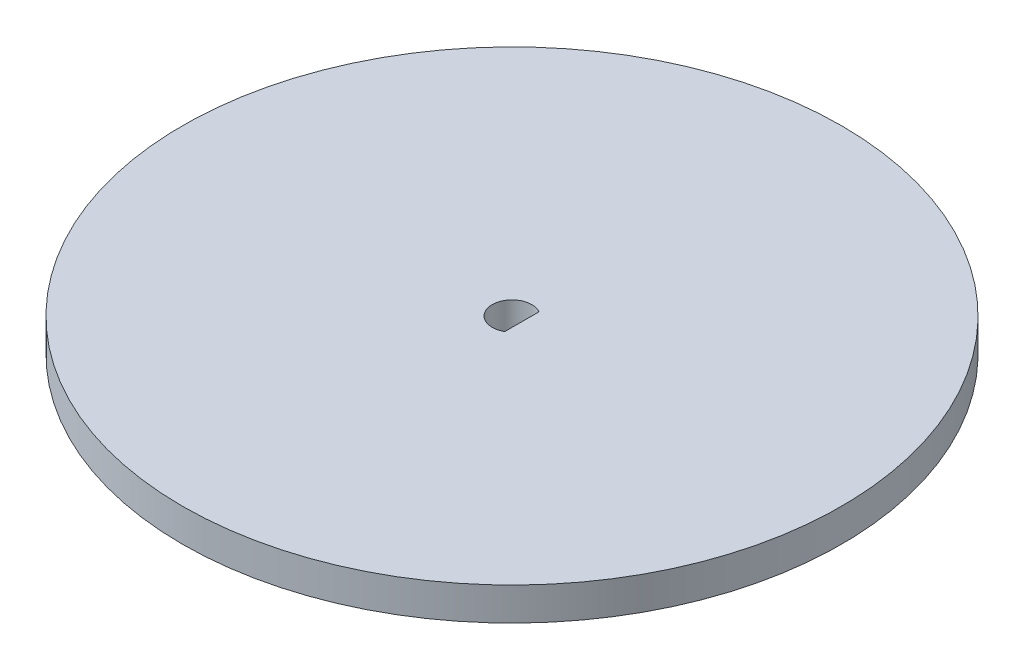
SolidWorks part; units mm, degrees
ref_plane "前视基准面" through (0, 0, 0) normal (0, 0, 1) x (1, 0, 0)
ref_plane "上视基准面" through (0, 0, 0) normal (0, 1, 0) x (1, 0, 0)
ref_plane "右视基准面" through (0, 0, 0) normal (1, 0, 0) x (0, 0, -1)
sketch "Sketch1" plane through (0, 0, 0) normal (0, 1, 0) x (1, 0, 0)
  line L0 (1.5, 4.1874) -> (1.5, -5.6419) construction
  line L1 (1.5, 2.5981) -> (1.5, -2.5981)
  line L2 (-50, 0) -> (25.889, 0) construction
  line L3 (0, 50) -> (0, -50) construction
  circle A0 centre (0, 0) radius 50
  arc A1 (1.5, 2.5981) -> (1.5, -2.5981) centre (0, 0) ccw
  dimension "D1" = 100
  dimension "D2" = 6
  dimension "D3" = 1.5
extrude "Boss-Extrude1" add sketch "Sketch1" along normal blind 5
